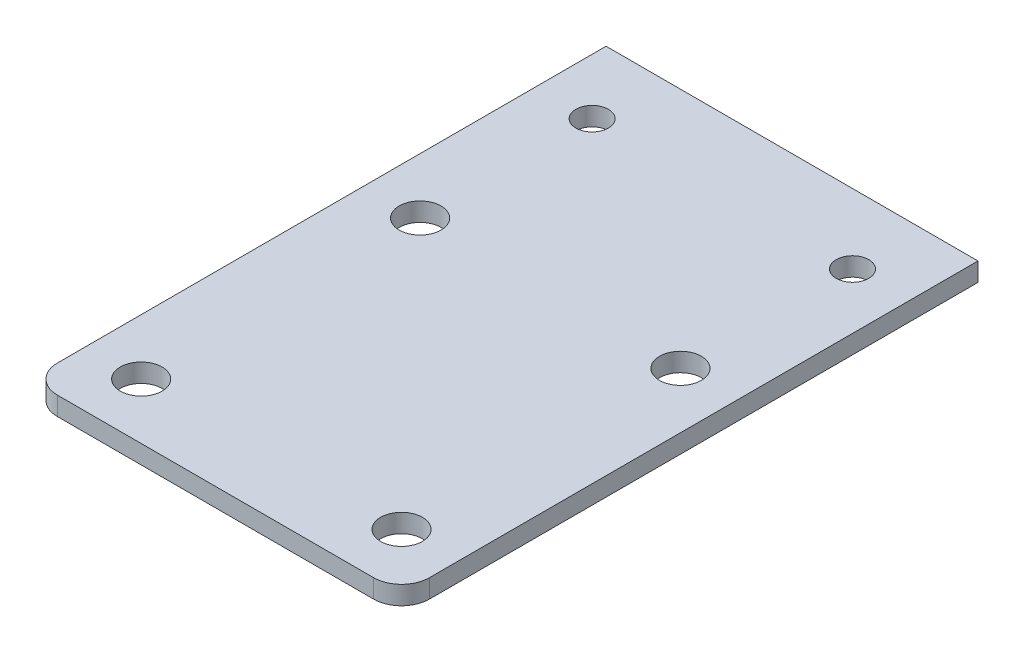
SolidWorks part; units mm, degrees
ref_plane "前视基准面" through (0, 0, 0) normal (0, 0, 1) x (1, 0, 0)
ref_plane "上视基准面" through (0, 0, 0) normal (0, 1, 0) x (1, 0, 0)
ref_plane "右视基准面" through (0, 0, 0) normal (1, 0, 0) x (0, 0, -1)
other "Configuration Table"
sketch "草图1" plane through (0, 0, 0) normal (0, 1, 0) x (1, 0, 0)
  line L0 (0, 0) -> (0, 30) construction
  line L1 (-14, 0) -> (14, 0)
  line L2 (14, 0) -> (14, 30)
  line L3 (14, 30) -> (-14, 30)
  line L4 (14, 30) -> (14, 48.5)
  line L5 (14, 48.5) -> (14, 56)
  line L6 (20, 56) -> (-20, 56)
  line L7 (20, 56) -> (20, -3)
  line L8 (17, -6) -> (-17, -6)
  line L9 (-20, 56) -> (-20, -3)
  line L10 (-14, 48.5) -> (-14, 56)
  line L11 (-14, 30) -> (-14, 48.5)
  line L12 (-14, 0) -> (-14, 30)
  circle A0 centre (14, 0) radius 2.25
  circle A1 centre (14, 30) radius 2.25
  circle A2 centre (14, 48.5) radius 1.75
  arc A3 (20, -3) -> (17, -6) centre (17, -3) cw
  arc A4 (-20, -3) -> (-17, -6) centre (-17, -3) ccw
  circle A5 centre (-14, 48.5) radius 1.75
  circle A6 centre (-14, 30) radius 2.25
  circle A7 centre (-14, 0) radius 2.25
  point P25 (0, -6)
  point P26 (0, 56)
  dimension "D2" = 4.5
  dimension "D4" = 4.5
  dimension "D6" = 3.5
  dimension "D10" = 3
  dimension "D1" = 28
  dimension "D3" = 30
  dimension "D5" = 48.5
  dimension "D7" = 56
  dimension "D8" = 6
  dimension "D9" = 6
extrude "凸台-拉伸1" add sketch "草图1" along normal blind 2 contours L1 L0 L3 A6 L12 A7 | L0 L1 A0 L2 A1 L3 | L1 A7 L12 A6 L11 A5 L10 L6 L9 A4 L8 A3 L7 L5 A2 L4 A1 L2 A0 | L11 A6 L3 A1 L4 A2 L5 L6 L10 A5
